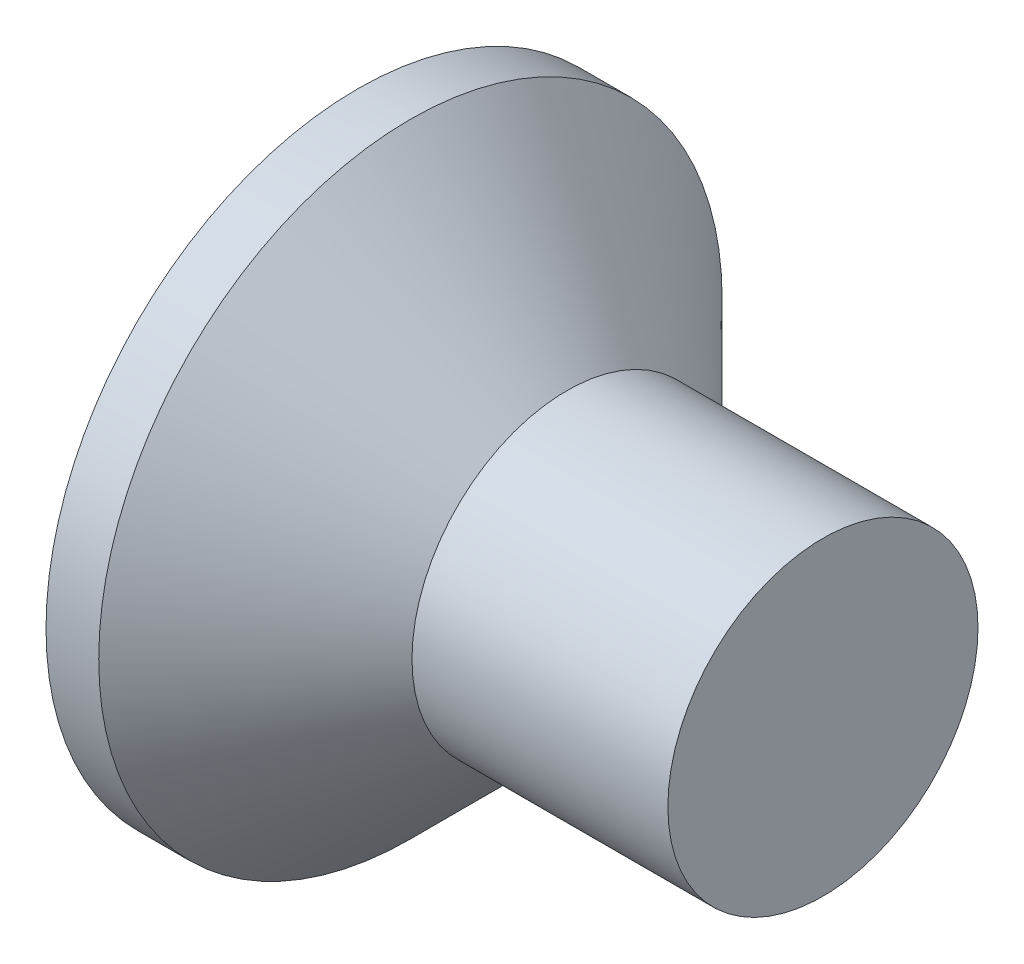
SolidWorks part; units mm, degrees
ref_plane "Front" through (0, 0, 0) normal (0, 0, 1) x (1, 0, 0)
ref_plane "Top" through (0, 0, 0) normal (0, 1, 0) x (1, 0, 0)
ref_plane "Right" through (0, 0, 0) normal (1, 0, 0) x (0, 0, -1)
sketch "Sketch1" plane through (0, 0, 0) normal (0, 0, 1) x (1, 0, 0)
  line L0 (6, 2) -> (4.1, 2)
  line L1 (4.1, 2) -> (2.7, 2)
  line L2 (2.7, 2) -> (0.68, 4.02)
  line L3 (0.68, 4.02) -> (0, 4.02)
  line L4 (6, 2) -> (6, 0)
  line L5 (4.5158, 0) -> (-89.8219, 0) construction
  line L6 (6, 0) -> (0, 0)
  line L7 (0, 4.02) -> (0, 0)
  dimension "D1" = 45
  dimension "dk" = 8.04
  dimension "l" = 6
  dimension "k" = 2.7
  dimension "a" = 1.4
  dimension "d" = 4
revolve "Base" add sketch "Sketch1" angle 360 about L5
cosmetic thread "ThreadCosmetic1" [suppressed] parameters "bb"=3.3
sketch "Sketch6" plane through (0, 0, 0) normal (1, 0, 0) x (0, 0, -1)
  line L0 (-1.9271, 0) -> (2.0512, 0) construction
  line L1 (0, 1.8651) -> (0, -2.0207) construction
  line L2 (0.46, 0.46) -> (0.46, 2.3)
  line L3 (0.46, 2.3) -> (-0.46, 2.3)
  line L4 (-0.46, 0.46) -> (-0.46, 2.3)
  line L5 (0.46, 0.46) -> (2.3, 0.46)
  line L6 (2.3, 0.46) -> (2.3, -0.46)
  line L7 (-2.3, 0.46) -> (-2.3, -0.46)
  line L8 (-0.46, 0.46) -> (-2.3, 0.46)
  line L9 (-0.46, -0.46) -> (-2.3, -0.46)
  line L10 (0.46, -0.46) -> (2.3, -0.46)
  line L11 (-0.46, -0.46) -> (-0.46, -2.3)
  line L12 (0.46, -2.3) -> (-0.46, -2.3)
  line L13 (0.46, -0.46) -> (0.46, -2.3)
  point P16 (-2.3, 0)
  point P17 (2.3, 0)
extrude "CrossRecess" cut sketch "Sketch6" along normal blind 1.35
draft "Draft9" type of draft neutral plane draft angle 30 faces to draft 4 face at (0.675, 2.3, 0) face at (0.675, 0, 2.3) face at (0.675, -2.3, 0) face at (0.675, 0, -2.3) neutral plane through (0, 4.02, 0) neutral plane normal (-1, 0, 0) parameters "D1"=30
fillet "Fillet5" radius 0.3 4 edges at (0.675, -0.46, -0.46) (0.675, 0.46, -0.46) (0.675, 0.46, 0.46) (0.675, -0.46, 0.46)
sketch "Sketch7" plane through (0, 0, 0) normal (1, 0, 0) x (0, 0, -1)
  line L0 (-2.0126, 0) -> (1.9757, 0) construction
  line L1 (0, 1.9314) -> (0, -2.0126) construction
  line L2 (0, 0) -> (1.5555, 1.5555) construction
  line L3 (0, 0.6874) -> (1.6263, 1.6263)
  line L4 (-1.5402, 1.5402) -> (0, 0) construction
  line L5 (0.6874, 0) -> (1.6263, 1.6263)
  line L6 (0, -0.6874) -> (1.6263, -1.6263)
  line L7 (0.6874, 0) -> (1.6263, -1.6263)
  line L8 (-0.6874, 0) -> (-1.6263, -1.6263)
  line L9 (0, -0.6874) -> (-1.6263, -1.6263)
  line L10 (-0.6874, 0) -> (-1.6263, 1.6263)
  line L11 (0, 0.6874) -> (-1.6263, 1.6263)
  dimension "D3" = 15
  dimension "m" = 4.6
extrude "Cut-Extrude3" [suppressed] cut sketch "Sketch7" along normal blind 10 draft 20
sketch "Sketch8" plane through (0, 0, 0) normal (0, 0, 1) x (1, 0, 0)
  line L0 (-32, 2.379) -> (-33.75, 2)
  line L1 (-33.75, 2) -> (2.7, 2)
  line L3 (6, -2) -> (6, 2) construction
  line L6 (2.7, 2) -> (2.7, 7)
  line L7 (2.7, 7) -> (-32, 7)
  line L8 (-32, 7) -> (-32, 2.379)
  line L9 (62.4753, 0.379) -> (52.9594, 0.379) construction
  dimension "D1" = 5
  dimension "x" = 1.75
  dimension "d" = 4
  dimension "THD_MINOR" = 3.242
  dimension "b" = 38
sketch "Sketch9" plane through (0, 0, 0) normal (0, 0, 1) x (1, 0, 0)
  line L0 (6, 1.6718) -> (6.1895, 2)
  line L1 (6.1895, 2) -> (6.1895, 2.379)
  line L2 (6.1895, 2.379) -> (5.8105, 2.379)
  line L3 (5.8105, 2.379) -> (5.8105, 2)
  line L4 (5.8105, 2) -> (6, 1.6718)
  line L5 (0, 0) -> (73.843, 0) construction
  line L6 (6, -2) -> (6, 2) construction
  dimension "D1" = 4
  dimension "D2" = 0.379
revolve "Cut-Revolve10" [suppressed] cut sketch "Sketch9" angle 360 about L5
pattern_linear "LPattern10" [suppressed] count 7 spacing 0.4548 along (1, 0, 0)
equation "\"D1@Sketch6\" = \"m@Sketch6\" / 5"
equation "\"D1@CrossRecess\" = \"k@Sketch1\" / 2"
equation "\"D1@Sketch9\" = \"d@Sketch1\""
equation "\"D2@Sketch9\" =  ( \"d@Sketch1\" - \"THD_MINOR@ThreadCosmetic1\" )  / 2"
equation "\"D3@LPattern10\" = \"D2@Sketch9\" * 1.2"
equation "\"D1@LPattern10\" = \"bb@ThreadCosmetic1\" / \"D3@LPattern10\" "
